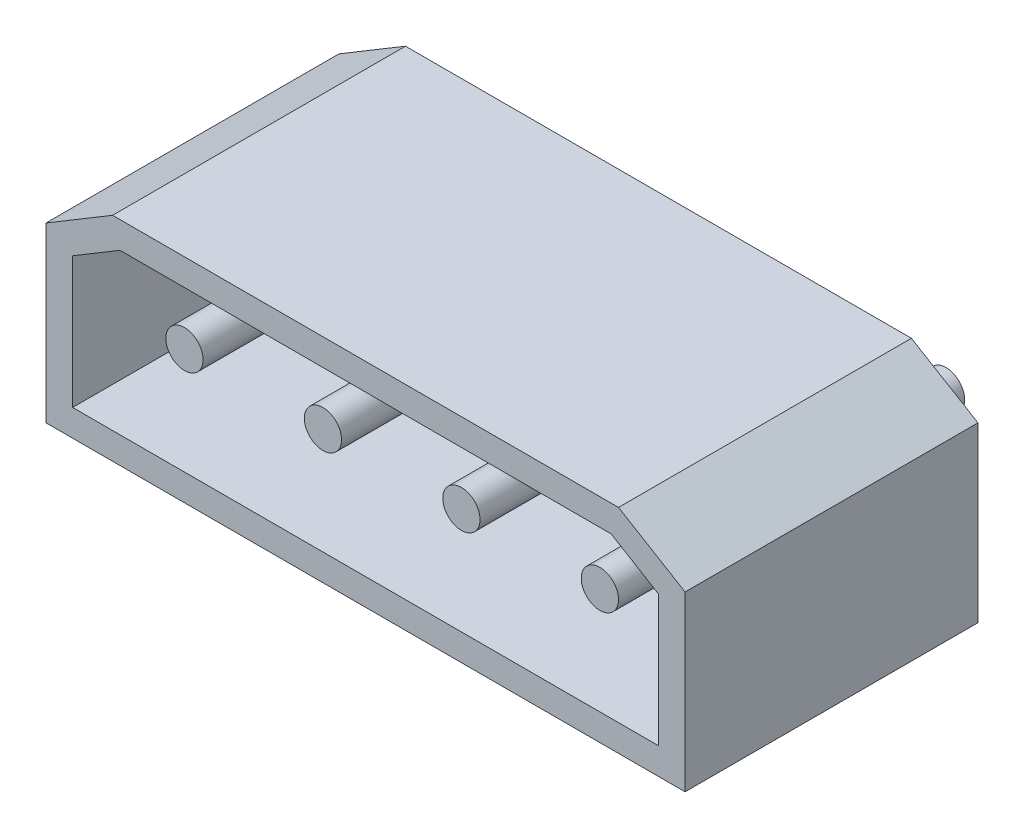
SolidWorks part; units mm, degrees
ref_plane "前视基准面" through (0, 0, 0) normal (0, 0, 1) x (1, 0, 0)
ref_plane "上视基准面" through (0, 0, 0) normal (0, 1, 0) x (1, 0, 0)
ref_plane "右视基准面" through (0, 0, 0) normal (1, 0, 0) x (0, 0, -1)
sketch "Model" plane through (0, 0, 0) normal (0, 0, 1) x (1, 0, 0)
  line L0 (2890.2783, 1613.5818) -> (2890.2783, 1604.5072) construction
  line L1 (2890.2783, 1611.2126) -> (2909.2783, 1611.2126)
  line L2 (2887.7783, 1609.7126) -> (2890.2783, 1611.2126)
  line L3 (2899.7783, 1611.2126) -> (2899.7783, 1603.2126) construction
  line L4 (2911.7783, 1609.7126) -> (2909.2783, 1611.2126)
  line L5 (2887.7783, 1603.2126) -> (2911.7783, 1603.2126)
  line L6 (2887.7783, 1603.2126) -> (2887.7783, 1609.7126)
  line L7 (2911.7783, 1603.2126) -> (2911.7783, 1609.7126)
  point P8 (2899.7783, 1603.2126)
  point P12 (2899.7783, 1611.2126)
  dimension "D1" = 24
  dimension "D2" = 9.5
  dimension "D3" = 8
  dimension "D4" = 6.5
extrude "凸台-拉伸1" add sketch "Model" along normal blind 11
sketch "草图2" plane through (0, 0, 11) normal (0, 0, 1) x (1, 0, 0)
  line L18 (2890.5553, 1610.2126) -> (2888.7783, 1609.1464)
  line L19 (2888.7783, 1609.1464) -> (2888.7783, 1604.2126)
  line L20 (2888.7783, 1604.2126) -> (2910.7783, 1604.2126)
  line L21 (2910.7783, 1604.2126) -> (2910.7783, 1609.1464)
  line L22 (2910.7783, 1609.1464) -> (2909.0013, 1610.2126)
  line L23 (2909.0013, 1610.2126) -> (2890.5553, 1610.2126)
  line L24 (2890.5553, 1610.2126) -> (2888.7783, 1609.1464)
  line L25 (2888.7783, 1609.1464) -> (2888.7783, 1604.2126)
  line L26 (2888.7783, 1604.2126) -> (2910.7783, 1604.2126)
  line L27 (2910.7783, 1604.2126) -> (2910.7783, 1609.1464)
  line L28 (2910.7783, 1609.1464) -> (2909.0013, 1610.2126)
  line L29 (2909.0013, 1610.2126) -> (2890.5553, 1610.2126)
  dimension "D1" = 1
extrude "切除-拉伸1" cut sketch "草图2" against normal blind 9
sketch "草图3" plane through (0, 0, 2) normal (0, 0, 1) x (1, 0, 0)
  line L0 (2890.2783, 1611.2126) -> (2890.2783, 1603.2126) construction
  line L1 (2887.7783, 1603.2126) -> (2911.7783, 1603.2126) construction
  line L2 (2890.2783, 1607.2126) -> (2915.0978, 1607.2126) construction
  line L3 (2899.7783, 1603.2126) -> (2899.7783, 1611.2126) construction
  line L4 (2909.2783, 1611.2126) -> (2890.2783, 1611.2126) construction
  circle A0 centre (2891.9783, 1607.2126) radius 0.7
  dimension "D1" = 15.6
  dimension "D2" = 1.4
extrude "凸台-拉伸2" add sketch "草图3" along normal mid plane 16
sketch "草图4" plane through (0, 0, -6) normal (0, 0, -1) x (-1, 0, 0)
  circle A0 centre (-2891.9783, 1607.2126) radius 1.5766
extrude "切除-拉伸2" cut sketch "草图4" against normal blind 3
pattern_linear "阵列(线性)1" count 4 spacing 5.2 along (1, 0, 0) of "切除-拉伸2", "凸台-拉伸2"
